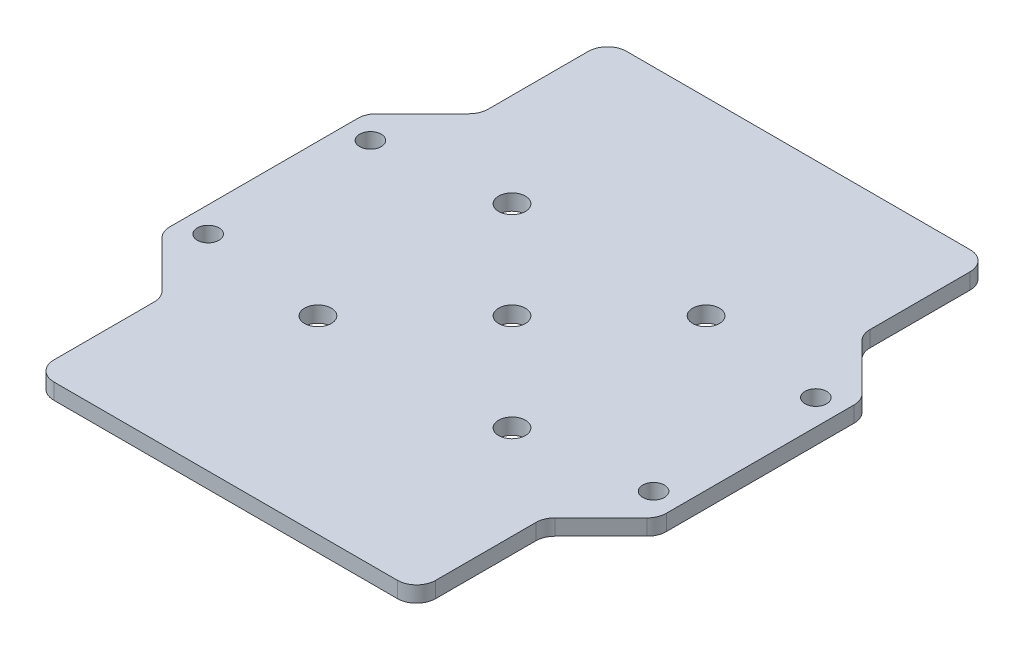
SolidWorks part; units mm, degrees
material "Thornel Mat VMA"
ref_plane "Front Plane" through (0, 0, 0) normal (0, 0, 1) x (1, 0, 0)
ref_plane "Top Plane" through (0, 0, 0) normal (0, 1, 0) x (1, 0, 0)
ref_plane "Right Plane" through (0, 0, 0) normal (1, 0, 0) x (0, 0, -1)
sketch "Sketch1" plane through (0, 0, 0) normal (0, 1, 0) x (1, 0, 0)
  line L0 (-30, 0) -> (-39, 0) construction
  line L1 (-30, 45) -> (30, 45)
  line L2 (-30, 45) -> (-30, -45)
  line L3 (-30, -45) -> (30, -45)
  line L4 (30, 45) -> (30, -45)
  line L5 (-30, 45) -> (30, -45) construction
  line L6 (-30, -45) -> (30, 45) construction
  line L7 (-15.25, -15.25) -> (15.25, -15.25) construction
  line L8 (-15.25, -15.25) -> (-15.25, 15.25) construction
  line L9 (-15.25, 15.25) -> (15.25, 15.25) construction
  line L10 (15.25, -15.25) -> (15.25, 15.25) construction
  line L11 (-15.25, -15.25) -> (15.25, 15.25) construction
  line L12 (-15.25, 15.25) -> (15.25, -15.25) construction
  line L13 (-39, -16) -> (-39, 16)
  line L14 (-39, 16) -> (-30, 25)
  line L15 (-39, -16) -> (-30, -25)
  line L16 (0, 0) -> (0, 36.025) construction
  line L17 (39, -16) -> (30, -25)
  line L18 (30, 0) -> (39, 0) construction
  line L19 (39, 16) -> (30, 25)
  line L20 (39, -16) -> (39, 16)
  point P0 (0, 0)
  point P6 (0, 0)
  dimension "D1" = 9
  dimension "56" = 60
  dimension "D2" = 30.5
  dimension "D3" = 90
  dimension "D4" = 16
  dimension "D5" = 45
extrude "Boss-Extrude1" add sketch "Sketch1" along normal mid plane 2.5
fillet "Fillet1" radius 3 12 edges at (30, 0, -45) (30, 0, 45) (-30, 0, 45) (-30, 0, -45) (30, 0, 25) (39, 0, 16) (39, 0, -16) (30, 0, -25) (-39, 0, -16) (-30, 0, -25) (-39, 0, 16) (-30, 0, 25)
hole_wizard "Ø4.2 (4.2) Diameter Hole1" positions "Sketch3" profile "Sketch4" hole size "Ø4.2" standard "ANSI Metric" end condition through all
sketch "Sketch3" plane through (0, 1.25, 0) normal (0, 1, 0) x (1, 0, 0)
  line L1 (-15.25, 15.25) -> (15.25, 15.25) construction
  line L2 (-15.25, 15.25) -> (-15.25, -15.25) construction
  line L3 (-15.25, -15.25) -> (15.25, -15.25) construction
  line L4 (15.25, 15.25) -> (15.25, -15.25) construction
  line L5 (-15.25, 15.25) -> (15.25, -15.25) construction
  line L6 (-15.25, -15.25) -> (15.25, 15.25) construction
  point P0 (0, 0)
  point P4 (0, 0)
  point P5 (15.25, -15.25)
  point P50 (-15.25, 15.25)
  point P51 (-15.25, -15.25)
  point P52 (15.25, 15.25)
  dimension "D1" = 30.5
sketch "Sketch4" plane through (0, 1.25, 0) normal (1, 0, 0) x (0, 0, 1)
  line L0 (0, 0) -> (0, 2.5)
  line L1 (0, 2.5) -> (2.1, 2.5)
  line L2 (2.1, 2.5) -> (2.1, 0)
  line L5 (2.1, 0) -> (0, 0)
  line L11 (0, -6.35) -> (0, 107.95) construction
  dimension "Thru Hole Dia." = 4.2
  dimension "Thru Hole Depth" = 2.5
hole_wizard "M3 Clearance Hole1" positions "Sketch5" profile "Sketch6" hole size "M3" standard "ANSI Metric" end condition through all
sketch "Sketch5" plane through (0, 1.25, 0) normal (0, 1, 0) x (1, 0, 0)
  point P0 (35, 12.75)
  point P3 (35, -12.75)
  point P6 (-35, -12.75)
  point P9 (-35, 12.75)
sketch "Sketch6" plane through (35, 1.25, -12.75) normal (1, 0, 0) x (0, 0, 1)
  line L0 (0, 0) -> (0, 2.5)
  line L1 (0, 2.5) -> (1.7, 2.5)
  line L2 (1.7, 2.5) -> (1.7, 0)
  line L5 (1.7, 0) -> (0, 0)
  line L11 (0, -6.35) -> (0, 107.95) construction
  dimension "Thru Hole Dia." = 3.4
  dimension "Thru Hole Depth" = 2.5
